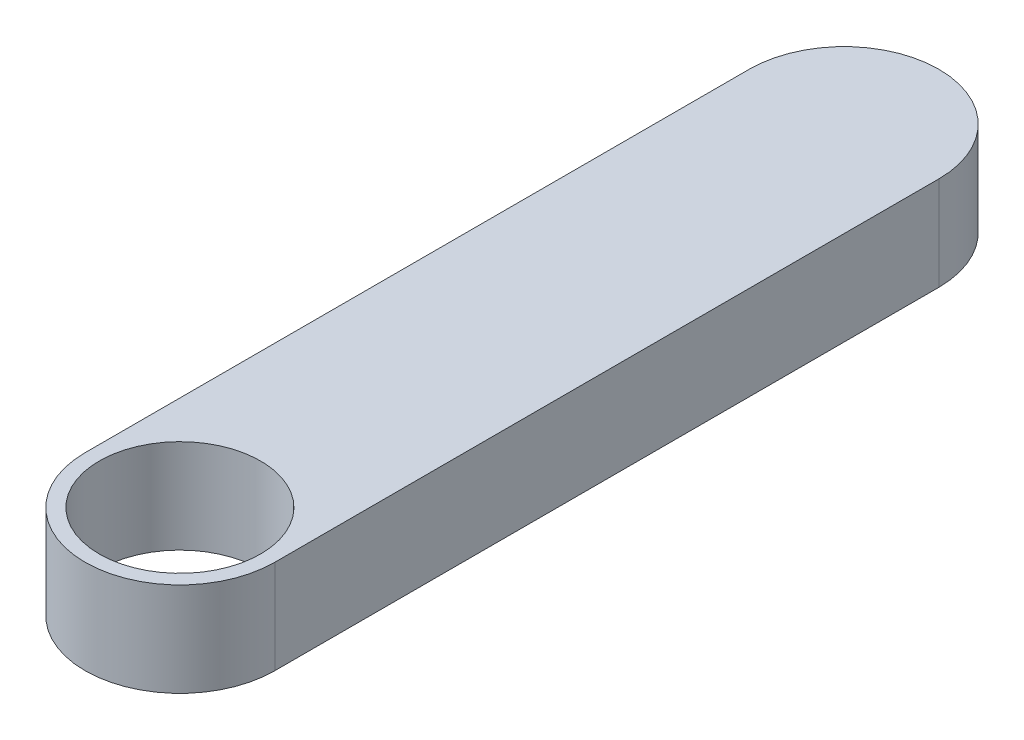
SolidWorks part; units mm, degrees
ref_plane "Front Plane" through (0, 0, 0) normal (0, 0, 1) x (1, 0, 0)
ref_plane "Top Plane" through (0, 0, 0) normal (0, 1, 0) x (1, 0, 0)
ref_plane "Right Plane" through (0, 0, 0) normal (1, 0, 0) x (0, 0, -1)
sketch "Sketch1" plane through (0, 0, 0) normal (0, 1, 0) x (1, 0, 0)
  line L0 (100, 0) -> (-100, 0)
  line L1 (100, 0) -> (100, 700)
  line L2 (-100, 0) -> (-100, 700)
  line L3 (100, 700) -> (-100, 700)
  circle A0 centre (0, 0) radius 100
  circle A1 centre (0, 700) radius 100
extrude "Boss-Extrude1" add sketch "Sketch1" along normal blind 99 contours L0 A0 | L0 A0 | A1 L2 A0 L1 | L3 A1 | L3 A1
sketch "Sketch2" plane through (0, 99, 0) normal (0, 1, 0) x (1, 0, 0)
  circle A0 centre (0, 0) radius 85
extrude "Cut-Extrude1" cut sketch "Sketch2" against normal blind 99
